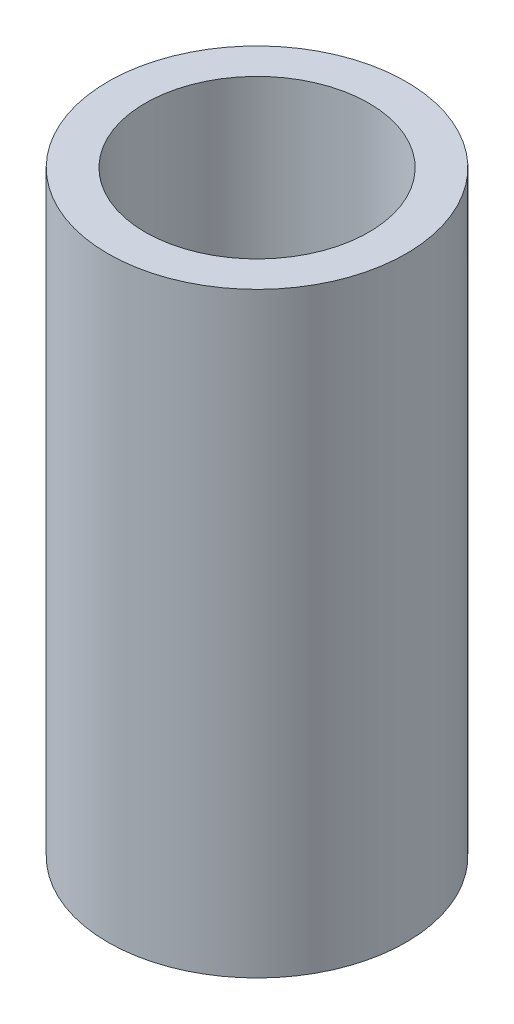
SolidWorks part; units mm, degrees
ref_plane "Front Plane" through (0, 0, 0) normal (0, 0, 1) x (1, 0, 0)
ref_plane "Top Plane" through (0, 0, 0) normal (0, 1, 0) x (1, 0, 0)
ref_plane "Right Plane" through (0, 0, 0) normal (1, 0, 0) x (0, 0, -1)
sketch "Sketch1" plane through (0, 0, 0) normal (0, 1, 0) x (1, 0, 0)
  circle A0 centre (0, 0) radius 12.7
extrude "Extrude1" add sketch "Sketch1" along normal blind 50.8
shell "Shell1" thickness 3.175
ref_plane "Plane1" through (0, 0, 0) normal (0, -1, 0) x (1, 0, 0)
sketch "Sketch3" plane through (0, 0, 0) normal (0, -1, 0) x (1, 0, 0)
  point P0 (0, 7.1437)
  point P1 (0, -7.1437)
  dimension "D1" = 7.1437
  dimension "D2" = 7.1437
hole_wizard "#4-40 Tapped Hole1" positions "3DSketch1" profile "Sketch5" tap size "#4-40" standard "Ansi Inch" end condition through all
sketch3d "3DSketch1"
  point P0 (0, 0, 7.1437)
sketch "Sketch5" plane through (0, 0, 7.1437) normal (1, 0, 0) x (0, 0, -1)
  line L0 (0, 0) -> (0, 50.8)
  line L1 (0, 50.8) -> (1.1303, 50.8)
  line L2 (1.1303, 50.8) -> (1.1303, 0)
  line L5 (1.1303, 0) -> (0, 0)
  line L11 (0, -6.35) -> (0, 107.95) construction
  dimension "Thru Tap Drill Dia." = 2.2606
  dimension "Thru Tap Drill Depth" = 50.8
cosmetic thread "Hole Thread1" parameters "D2"=2.8448
hole_wizard "#4-40 Tapped Hole2" positions "3DSketch2" profile "Sketch7" tap size "#4-40" standard "Ansi Inch" end condition through all
sketch3d "3DSketch2"
  point P0 (0, 0, -7.1437)
sketch "Sketch7" plane through (0, 0, -7.1437) normal (1, 0, 0) x (0, 0, -1)
  line L0 (0, 0) -> (0, 50.8)
  line L1 (0, 50.8) -> (1.1303, 50.8)
  line L2 (1.1303, 50.8) -> (1.1303, 0)
  line L5 (1.1303, 0) -> (0, 0)
  line L11 (0, -6.35) -> (0, 107.95) construction
  dimension "Thru Tap Drill Dia." = 2.2606
  dimension "Thru Tap Drill Depth" = 50.8
cosmetic thread "Hole Thread2" parameters "D2"=2.8448
sketch "Sketch8" plane through (0, 0, 0) normal (0, -1, 0) x (1, 0, 0)
  circle A0 centre (0, 0) radius 3.5719
  dimension "D1" = 7.1437
extrude "Cut-Extrude1" cut sketch "Sketch8" against normal through all
sketch "Sketch9" plane through (0, 0, 0) normal (0, -1, 0) x (1, 0, 0)
  line L0 (0, 0) -> (0, -7.1437)
